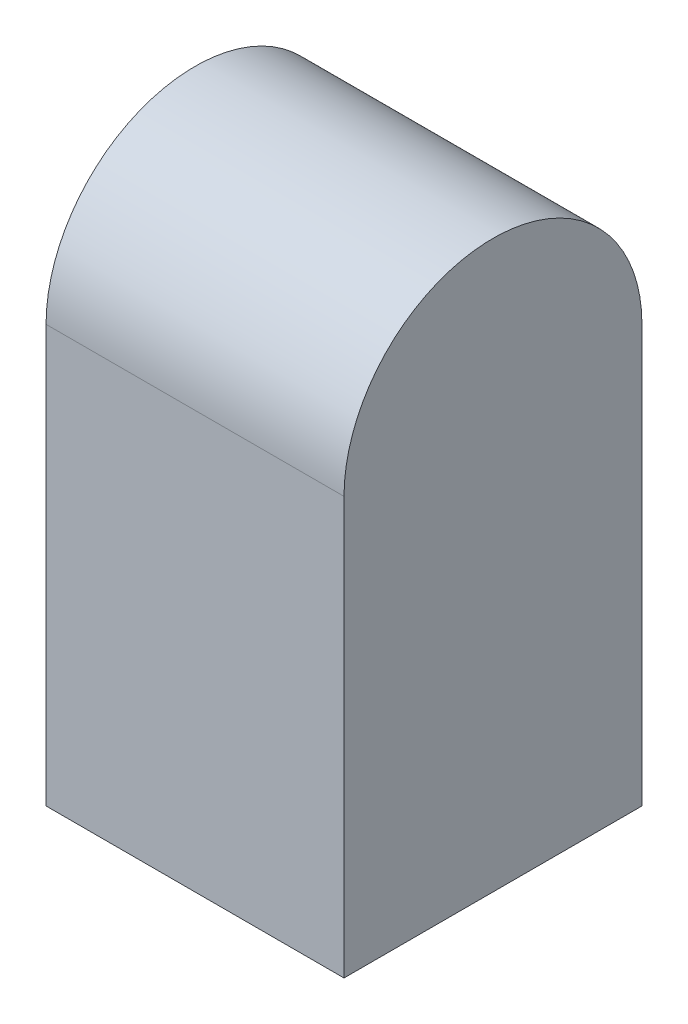
SolidWorks part; units mm, degrees
ref_plane "Plan de face" through (0, 0, 0) normal (0, 0, 1) x (1, 0, 0)
ref_plane "Plan de dessus" through (0, 0, 0) normal (0, 1, 0) x (1, 0, 0)
ref_plane "Plan de droite" through (0, 0, 0) normal (1, 0, 0) x (0, 0, -1)
sketch "Esquisse1" plane through (0, 0, 0) normal (0, 1, 0) x (1, 0, 0)
  line L1 (-12.5, 12.5) -> (12.5, 12.5)
  line L2 (-12.5, 12.5) -> (-12.5, -12.5)
  line L3 (-12.5, -12.5) -> (12.5, -12.5)
  line L4 (12.5, 12.5) -> (12.5, -12.5)
  dimension "D1" = 25
  dimension "D2" = 12.5
  dimension "D3" = 12.5
extrude "Boss.-Extru.1" add sketch "Esquisse1" along normal blind 35
sketch "Esquisse2" plane through (12.5, 0, 0) normal (1, 0, 0) x (0, 0, -1)
  line L0 (-12.5, 35) -> (12.5, 35) construction
  line L1 (-12.5, 35) -> (12.5, 35)
  arc A0 (12.5, 35) -> (-12.5, 35) centre (0, 35) ccw
extrude "Boss.-Extru.2" add sketch "Esquisse2" against normal blind 25
